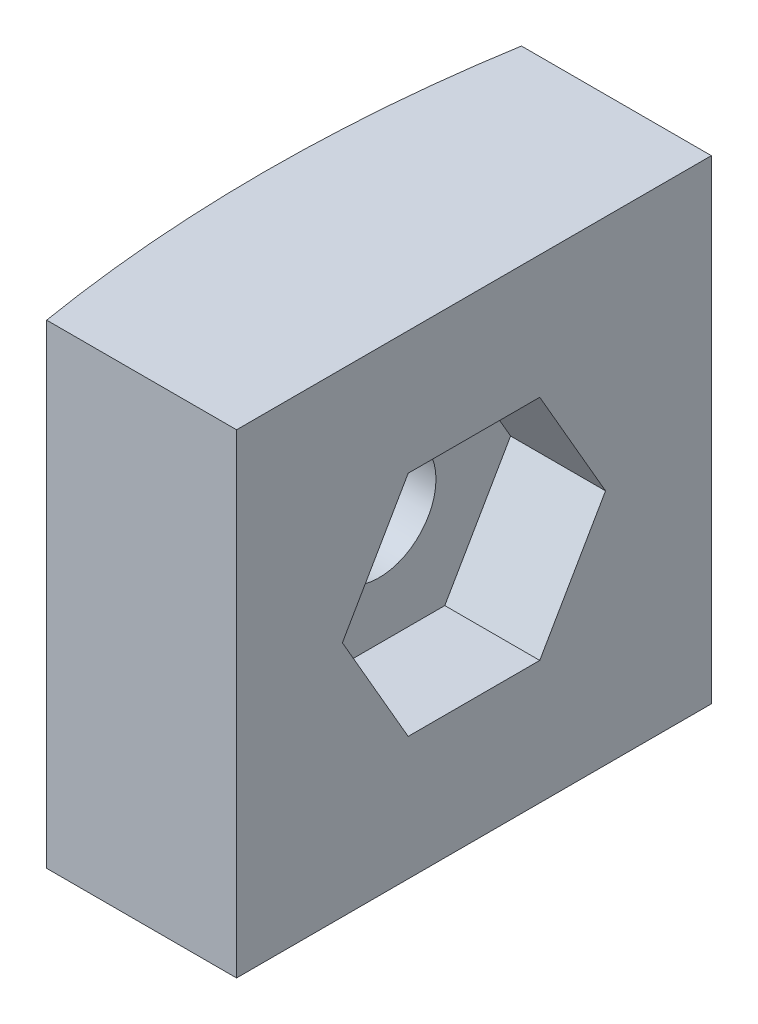
SolidWorks part; units mm, degrees
material "ABS"
ref_plane "Front Plane" through (0, 0, 0) normal (0, 0, 1) x (1, 0, 0)
ref_plane "Top Plane" through (0, 0, 0) normal (0, 1, 0) x (1, 0, 0)
ref_plane "Right Plane" through (0, 0, 0) normal (1, 0, 0) x (0, 0, -1)
sketch "Sketch1" plane through (0, 0, 0) normal (0, 1, 0) x (1, 0, 0)
  line L0 (-65.5047, 11.4784) -> (-65.5047, -13.5216)
  line L1 (-65.5047, 11.4784) -> (-70.5047, 11.4784)
  line L2 (-65.5047, -13.5216) -> (-70.5047, -13.5216)
  arc A0 (-70.5047, 11.4784) -> (-70.5047, -13.5216) centre (4.663, -1.0216) ccw
  point P3 (-65.5047, -1.0216)
  dimension "D1" = 25
  dimension "D3" = 152.4
  dimension "D2" = 5
extrude "Boss-Extrude1" add sketch "Sketch1" along normal blind 25
sketch "Sketch2" plane through (-65.5047, 0, 0) normal (1, 0, 0) x (0, 0, -1)
  line L0 (-13.5216, 25) -> (-13.5216, 0) construction
  line L1 (-13.5216, 25) -> (11.4784, 25) construction
  circle A0 centre (-1.0216, 12.5) radius 3
  dimension "D1" = 6
  dimension "D2" = 12.5
  dimension "D3" = 12.5
extrude "Cut-Extrude1" cut sketch "Sketch2" against normal blind 25
sketch "Sketch3" plane through (-65.5047, 0, 0) normal (1, 0, 0) x (0, 0, -1)
  line L0 (11.4784, 25) -> (11.4784, 0) construction
  line L1 (-13.5216, 0) -> (11.4784, 0) construction
  line L2 (-13.5216, 25) -> (-13.5216, 0) construction
  line L3 (-13.5216, 25) -> (11.4784, 25) construction
  line L4 (11.4784, 25) -> (11.4784, 0)
  line L5 (-13.5216, 0) -> (11.4784, 0)
  line L6 (-13.5216, 25) -> (-13.5216, 0)
  line L7 (-13.5216, 25) -> (11.4784, 25)
  line L9 (5.9066, 12.5) -> (2.4425, 18.5)
  line L10 (2.4425, 18.5) -> (-4.4857, 18.5)
  line L11 (-4.4857, 18.5) -> (-7.9498, 12.5)
  line L12 (-7.9498, 12.5) -> (-4.4857, 6.5)
  line L13 (-4.4857, 6.5) -> (2.4425, 6.5)
  line L14 (2.4425, 6.5) -> (5.9066, 12.5)
  circle A0 centre (-1.0216, 12.5) radius 3 construction
  circle A1 centre (-1.0216, 12.5) radius 3 construction
  circle A2 centre (-1.0216, 12.5) radius 6 construction
  dimension "D1" = 12
extrude "Boss-Extrude2" add sketch "Sketch3" along normal blind 5
